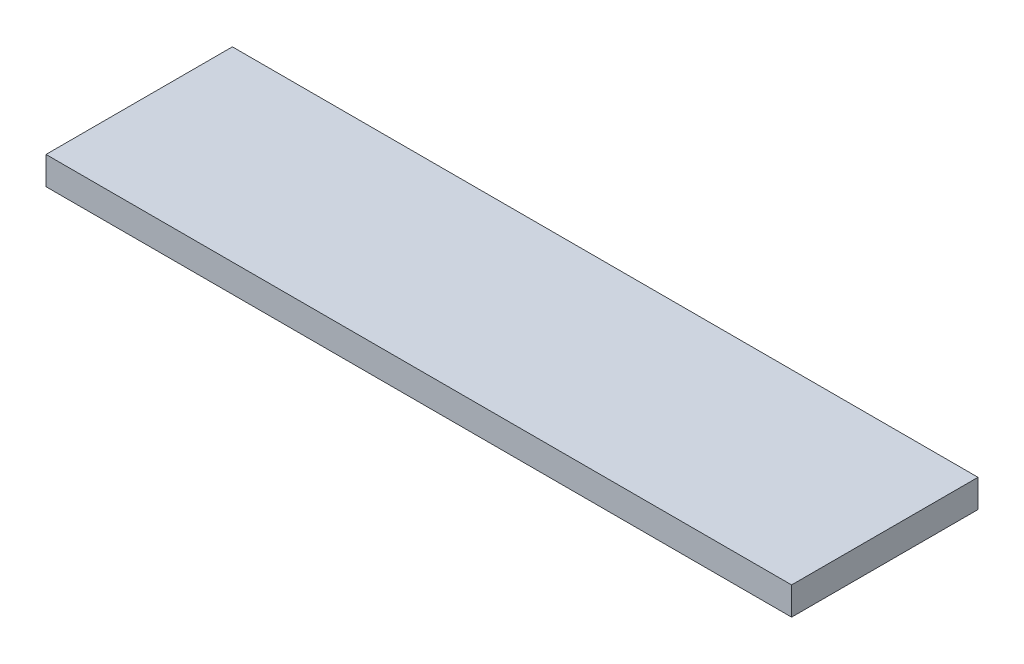
SolidWorks part; units mm, degrees
ref_plane "Plan de face" through (0, 0, 0) normal (0, 0, 1) x (1, 0, 0)
ref_plane "Plan de dessus" through (0, 0, 0) normal (0, 1, 0) x (1, 0, 0)
ref_plane "Plan de droite" through (0, 0, 0) normal (1, 0, 0) x (0, 0, -1)
sketch "Esquisse1" plane through (0, 0, 0) normal (0, 1, 0) x (1, 0, 0)
  line L1 (200, -50) -> (-200, -50)
  line L2 (200, -50) -> (200, 50)
  line L3 (200, 50) -> (-200, 50)
  line L4 (-200, -50) -> (-200, 50)
  line L5 (200, -50) -> (-200, 50) construction
  line L6 (200, 50) -> (-200, -50) construction
  point P0 (0, 0)
  dimension "D1" = 100
  dimension "D2" = 400
extrude "Boss.-Extru.1" add sketch "Esquisse1" along normal blind 15
